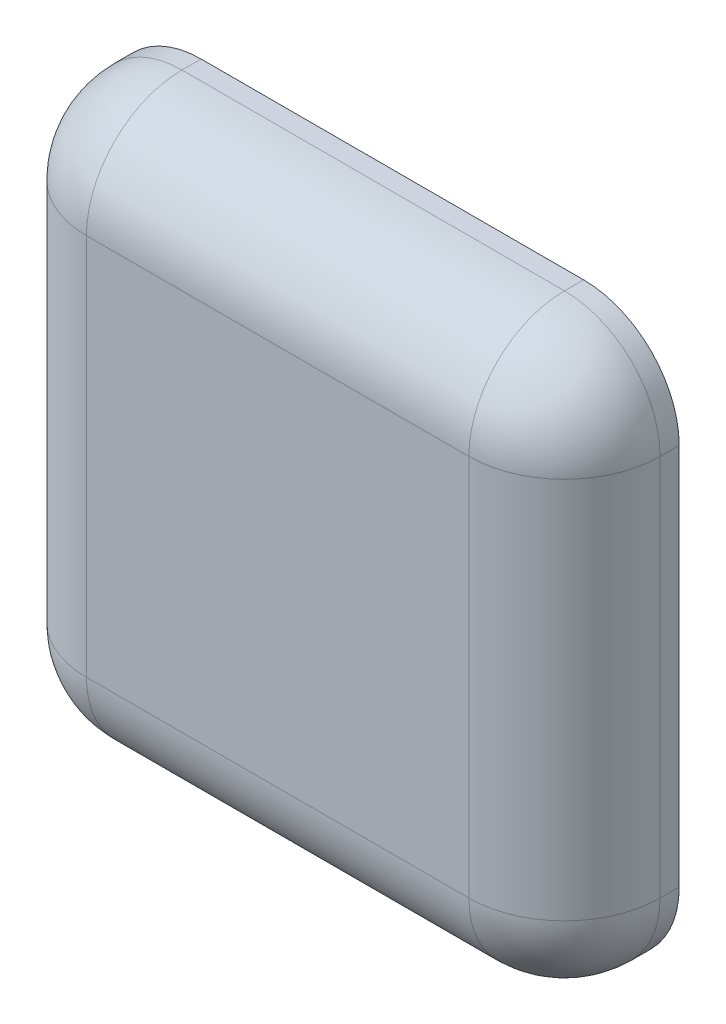
SolidWorks part; units mm, degrees
ref_plane "Front Plane" through (0, 0, 0) normal (0, 0, 1) x (1, 0, 0)
ref_plane "Top Plane" through (0, 0, 0) normal (0, 1, 0) x (1, 0, 0)
ref_plane "Right Plane" through (0, 0, 0) normal (1, 0, 0) x (0, 0, -1)
sketch "Sketch1" plane through (0, 0, 0) normal (0, 0, 1) x (1, 0, 0)
  line L0 (-81.4815, 117.5926) -> (-81.4815, -182.4074)
  line L1 (-81.4815, -182.4074) -> (218.5185, -182.4074)
  line L2 (218.5185, -182.4074) -> (218.5185, 117.5926)
  line L3 (218.5185, 117.5926) -> (-81.4815, 117.5926)
  dimension "D1" = 300
  dimension "D2" = 300
extrude "Boss-Extrude1" add sketch "Sketch1" along normal blind 60
fillet "Fillet1" radius 50 8 edges at (218.5185, -32.4074, 60) (68.5185, -182.4074, 60) (68.5185, 117.5926, 60) (-81.4815, -32.4074, 60) (-81.4815, -182.4074, 30) (-81.4815, 117.5926, 30) (218.5185, 117.5926, 30) (218.5185, -182.4074, 30)
